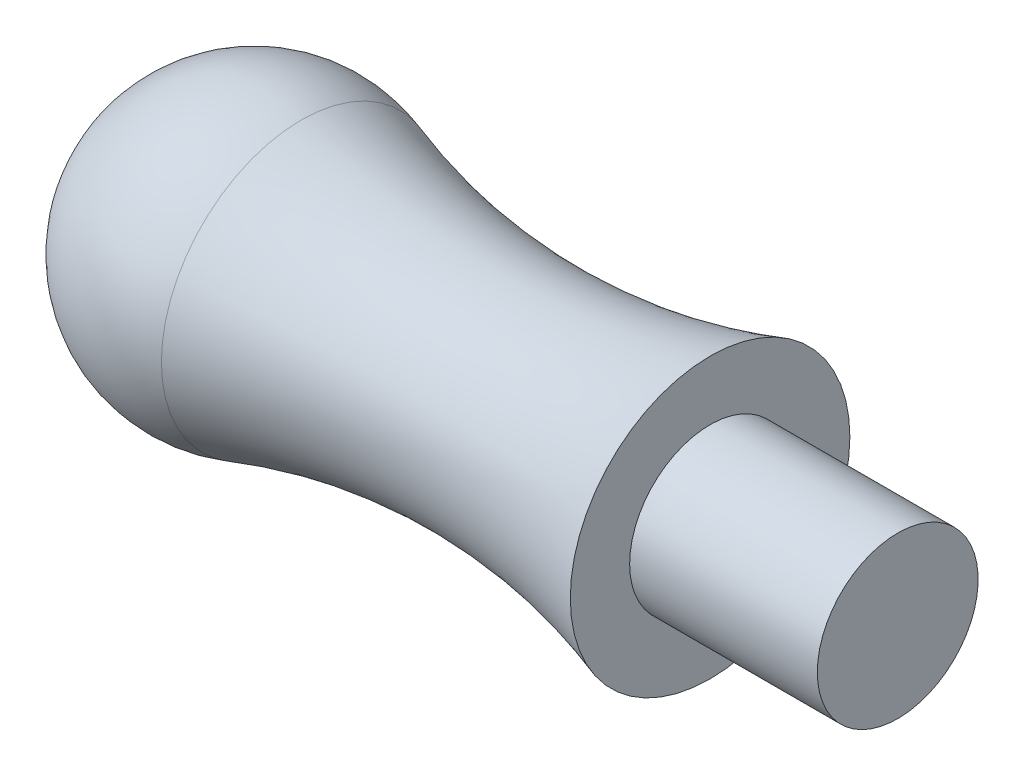
SolidWorks part; units mm, degrees
ref_plane "Front Plane" through (0, 0, 0) normal (0, 0, 1) x (1, 0, 0)
ref_plane "Top Plane" through (0, 0, 0) normal (0, 1, 0) x (1, 0, 0)
ref_plane "Right Plane" through (0, 0, 0) normal (1, 0, 0) x (0, 0, -1)
sketch "Sketch1" plane through (0, 0, 0) normal (0, 0, 1) x (1, 0, 0)
  line L0 (0, 0) -> (17, 0) construction
  line L1 (17, 5.2149) -> (17, 3)
  line L2 (17, 3) -> (24, 3)
  line L3 (24, 3) -> (24, 0)
  line L4 (24, 0) -> (-5.5, 0)
  arc A0 (1.7477, 5.2149) -> (-5.5, 0) centre (0, 0) ccw
  arc A1 (1.7477, 5.2149) -> (17, 5.2149) centre (9.3738, 27.9711) ccw
  point P3 (17, 1.6849)
  point P5 (17, 6.6826)
  point P6 (0, 0)
  point P13 (17, 5.2182)
  point P14 (0, 0)
  point P15 (0, 0)
  dimension "D1" = 11
  dimension "D2" = 48
  dimension "D3" = 3
  dimension "D4" = 7
  dimension "D5" = 24
revolve "Revolve1" add sketch "Sketch1" angle 360 about L0
cosmetic thread "Cosmetic Thread1" parameters "D1"=7, "D2"=4.891
